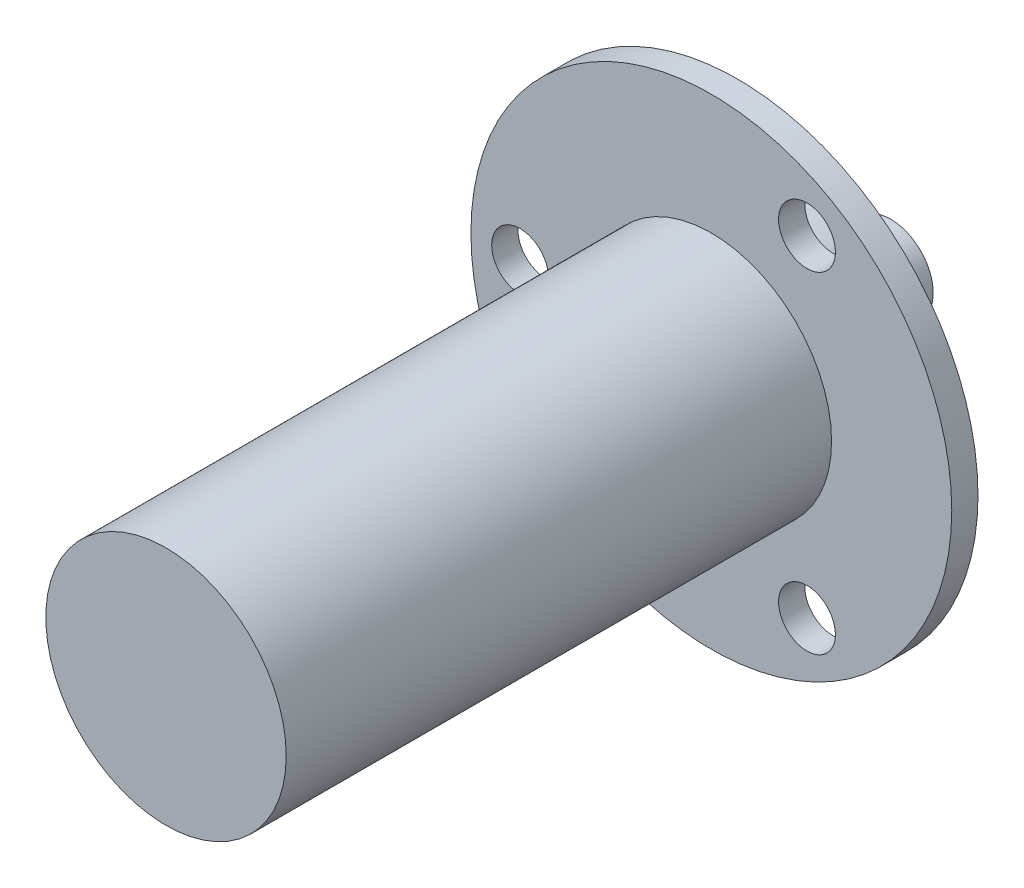
SolidWorks part; units mm, degrees
ref_plane "Plan de face" through (0, 0, 0) normal (0, 0, 1) x (1, 0, 0)
ref_plane "Plan de dessus" through (0, 0, 0) normal (0, 1, 0) x (1, 0, 0)
ref_plane "Plan de droite" through (0, 0, 0) normal (1, 0, 0) x (0, 0, -1)
sketch "Esquisse1" plane through (0, 0, 0) normal (0, 0, 1) x (1, 0, 0)
  circle A0 centre (0, 0) radius 11
  dimension "D1" = 22
extrude "Boss.-Extru.1" add sketch "Esquisse1" along normal blind 49.9
sketch "Esquisse2" plane through (0, 0, 0) normal (0, 0, -1) x (-1, 0, 0)
  circle A0 centre (0, 0) radius 22
  circle A1 centre (17.5, 0) radius 2.6
  circle A3 centre (-8.75, -15.1554) radius 2.6
  circle A4 centre (-8.75, 15.1554) radius 2.6
  point P12 (0, 0)
  dimension "D1" = 44
  dimension "D3" = 5.2
  dimension "D2" = 17.5
  dimension "D4" = 3
extrude "Boss.-Extru.2" add sketch "Esquisse2" along normal blind 2.4
sketch "Esquisse3" plane through (0, 0, -2.4) normal (0, 0, -1) x (-1, 0, 0)
  circle A0 centre (0, 0) radius 11
  dimension "D1" = 22
extrude "Boss.-Extru.3" add sketch "Esquisse3" along normal blind 5
sketch "Esquisse4" plane through (0, 0, -7.4) normal (0, 0, -1) x (-1, 0, 0)
  circle A0 centre (0, 0) radius 3.9
  dimension "D1" = 7.8
extrude "Boss.-Extru.4" add sketch "Esquisse4" along normal blind 9
